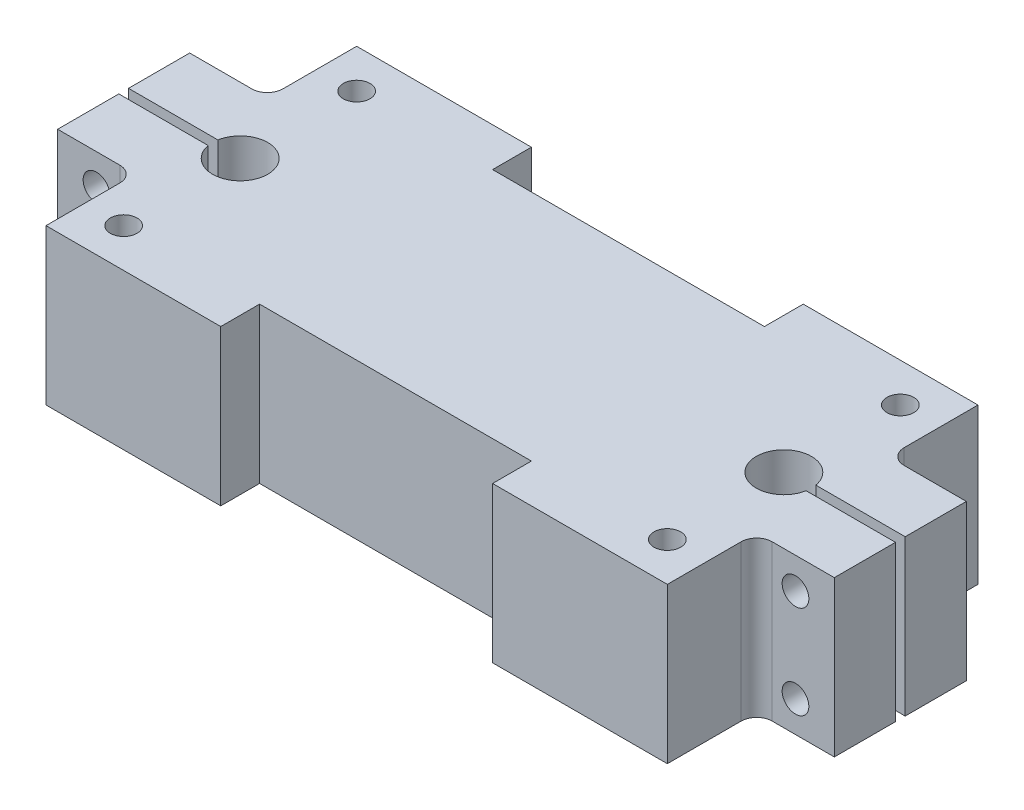
SolidWorks part; units mm, degrees
ref_plane "Front Plane" through (0, 0, 0) normal (0, 0, 1) x (1, 0, 0)
ref_plane "Top Plane" through (0, 0, 0) normal (0, 1, 0) x (1, 0, 0)
ref_plane "Right Plane" through (0, 0, 0) normal (1, 0, 0) x (0, 0, -1)
sketch "Sketch1" plane through (0, 0, 0) normal (0, 1, 0) x (1, 0, 0)
  line L1 (-63.5, 25.4) -> (63.5, 25.4)
  line L2 (-63.5, 25.4) -> (-63.5, -25.4)
  line L3 (-63.5, -25.4) -> (63.5, -25.4)
  line L4 (63.5, 25.4) -> (63.5, -25.4)
  dimension "D1" = 50.8
  dimension "D2" = 127
  dimension "D3" = 63.5
  dimension "D4" = 25.4
extrude "Boss-Extrude1" add sketch "Sketch1" along normal blind 25.4 contours L2 L3 L4 L1
sketch "Sketch2" plane through (0, 25.4, 0) normal (0, 1, 0) x (1, 0, 0)
  line L0 (-63.5, 25.4) -> (-63.5, -25.4) construction
  line L1 (63.5, 25.4) -> (63.5, -25.4) construction
  line L2 (-63.5, -25.4) -> (63.5, -25.4) construction
  circle A0 centre (-44.45, 0) radius 4.5085
  circle A1 centre (44.45, 0) radius 4.5085
  point P6 (63.5, 0)
  dimension "D1" = 9.017
  dimension "D2" = 9.017
  dimension "D3" = 19.05
  dimension "D4" = 19.05
  dimension "D5" = 25.4
  dimension "D6" = 25.4
extrude "Cut-Extrude1" cut sketch "Sketch2" against normal through all
sketch "Sketch3" plane through (0, 25.4, 0) normal (0, 1, 0) x (1, 0, 0)
  line L1 (-44.45, 0.7937) -> (-63.5, 0.7937)
  line L2 (-44.45, 0.7937) -> (-44.45, -0.7938)
  line L3 (-44.45, -0.7938) -> (-63.5, -0.7938)
  line L4 (-63.5, 0.7937) -> (-63.5, -0.7938)
  line L5 (-63.5, 25.4) -> (63.5, 25.4) construction
  line L7 (63.5, 0.7937) -> (63.5, -0.7938)
  line L8 (44.45, -0.7938) -> (63.5, -0.7938)
  line L9 (44.45, 0.7937) -> (44.45, -0.7938)
  line L10 (44.45, 0.7937) -> (63.5, 0.7937)
  dimension "D1" = 0.7937
  dimension "D2" = 1.5875
  dimension "D3" = 19.05
  dimension "D4" = 44.45
  dimension "D5" = 1.5875
  dimension "D6" = 24.6062
  dimension "D7" = 19.05
  dimension "D8" = 44.45
  dimension "D9" = 1.5875
extrude "Cut-Extrude2" cut sketch "Sketch3" against normal through all
sketch "Sketch4" plane through (0, 25.4, 0) normal (0, 1, 0) x (1, 0, 0)
  line L1 (-63.5, 25.4) -> (-50.8, 25.4)
  line L2 (-63.5, 25.4) -> (-63.5, 10.795)
  line L3 (-63.5, 10.795) -> (-50.8, 10.795)
  line L4 (-50.8, 25.4) -> (-50.8, 10.795)
  line L5 (-63.5, -25.4) -> (-50.8, -25.4)
  line L6 (-63.5, -25.4) -> (-63.5, -10.795)
  line L7 (-63.5, -10.795) -> (-50.8, -10.795)
  line L8 (-50.8, -25.4) -> (-50.8, -10.795)
  line L9 (0, 25.4) -> (0, -25.4)
  line L10 (-63.5, 25.4) -> (63.5, 25.4) construction
  line L11 (-63.5, -25.4) -> (63.5, -25.4) construction
  line L12 (50.8, -25.4) -> (50.8, -10.795)
  line L13 (63.5, -10.795) -> (50.8, -10.795)
  line L14 (63.5, -25.4) -> (63.5, -10.795)
  line L15 (63.5, -25.4) -> (50.8, -25.4)
  line L16 (50.8, 25.4) -> (50.8, 10.795)
  line L17 (63.5, 10.795) -> (50.8, 10.795)
  line L18 (63.5, 25.4) -> (63.5, 10.795)
  line L19 (63.5, 25.4) -> (50.8, 25.4)
  line M3 (63.5, 0.7937) -> (63.5, 25.4)
  line M4 (63.5, 25.4) -> (-63.5, 25.4)
  line M5 (-63.5, 25.4) -> (-63.5, 0.7937)
  line M9 (-63.5, -0.7938) -> (-63.5, -25.4)
  line M10 (-63.5, -25.4) -> (63.5, -25.4)
  line M11 (63.5, -25.4) -> (63.5, -0.7938)
  dimension "D1" = 12.7
  dimension "D2" = 21.59
  dimension "D3" = 14.605
  dimension "D4" = 0
extrude "Cut-Extrude3" cut sketch "Sketch4" against normal through all contours L8 L7 M10 M9 | L4 L3 M4 M5 | L17 L16 M3 M4 | L13 L12 M11 M10
sketch "Sketch5" plane through (0, 0, 10.795) normal (0, 0, 1) x (1, 0, 0)
  line L0 (-57.15, 25.4) -> (-57.15, 0)
  line L1 (-63.5, 25.4) -> (-50.8, 25.4) construction
  line L2 (-63.5, 0) -> (-50.8, 0) construction
  line L3 (57.15, 25.4) -> (57.15, 0)
  line L4 (63.5, 25.4) -> (50.8, 25.4) construction
  line L5 (63.5, 0) -> (50.8, 0) construction
  point P12 (-57.15, 20.32)
  point P13 (-57.15, 5.08)
  point P14 (57.15, 5.08)
  point P15 (57.15, 20.32)
  dimension "D1" = 5.08
  dimension "D2" = 5.08
  dimension "D3" = 5.08
  dimension "D4" = 5.08
hole_wizard "11/64 (0.17188) Diameter Hole1" positions "3DSketch1" profile "Sketch6" hole size "11/64" standard "ANSI Inch"
sketch3d "3DSketch1"
  point P0 (-57.15, 20.32, 10.795)
  point P3 (-57.15, 5.08, 10.795)
  point P6 (57.15, 20.32, 10.795)
  point P9 (57.15, 5.08, 10.795)
sketch "Sketch6" plane through (-57.15, 20.32, 10.795) normal (1, 0, 0) x (0, -1, 0)
  line L0 (0, 0) -> (0, 26.7116)
  line L1 (0, 26.7116) -> (2.1829, 25.4)
  line L2 (2.1829, 25.4) -> (2.1829, 0)
  line L5 (2.1829, 0) -> (0, 0)
  line L10 (0, 26.7116) -> (-2.1829, 25.4) construction
  line L11 (0, -6.35) -> (0, 107.95) construction
  dimension "Hole Dia." = 4.3658
  dimension "Hole Depth" = 25.4
  dimension "Drill Angle" = 118
fillet "Fillet3" radius 2.54 4 edges at (50.8, 12.7, 10.795) (50.8, 12.7, -10.795) (-50.8, 12.7, -10.795) (-50.8, 12.7, 10.795)
sketch "Sketch7" plane through (0, 25.4, 0) normal (0, 1, 0) x (1, 0, 0)
  line L0 (-44.45, 25.4) -> (-44.45, -25.4)
  line L1 (-50.8, 25.4) -> (50.8, 25.4) construction
  line L2 (-50.8, -25.4) -> (50.8, -25.4) construction
  line L3 (44.45, 0) -> (44.45, 25.4)
  line L4 (44.45, 25.4) -> (44.45, -25.4)
  point P7 (-44.45, 19.05)
  point P8 (-44.45, -19.05)
  point P12 (44.45, 19.05)
  point P14 (44.45, -19.05)
  dimension "D1" = 6.35
  dimension "D2" = 6.35
  dimension "D3" = 6.35
  dimension "D4" = 6.35
hole_wizard "11/64 (0.17188) Diameter Hole2" positions "3DSketch2" profile "Sketch8" hole size "11/64" standard "ANSI Inch"
sketch3d "3DSketch2"
  point P0 (-44.45, 25.4, -19.05)
  point P3 (-44.45, 25.4, 19.05)
  point P6 (44.45, 25.4, 19.05)
  point P9 (44.45, 25.4, -19.05)
sketch "Sketch8" plane through (-44.45, 25.4, -19.05) normal (1, 0, 0) x (0, 0, 1)
  line L0 (0, 0) -> (0, 26.7116)
  line L1 (0, 26.7116) -> (2.1829, 25.4)
  line L2 (2.1829, 25.4) -> (2.1829, 0)
  line L5 (2.1829, 0) -> (0, 0)
  line L10 (0, 26.7116) -> (-2.1829, 25.4) construction
  line L11 (0, -6.35) -> (0, 107.95) construction
  dimension "Hole Dia." = 4.3658
  dimension "Hole Depth" = 25.4
  dimension "Drill Angle" = 118
sketch "Sketch9" plane through (0, 25.4, 0) normal (0, 1, 0) x (1, 0, 0)
  line L0 (-50.8, -25.4) -> (50.8, -25.4) construction
  line L1 (-22.225, -19.05) -> (22.225, -19.05)
  line L2 (-22.225, -19.05) -> (-22.225, -25.4)
  line L3 (-22.225, -25.4) -> (22.225, -25.4)
  line L4 (22.225, -19.05) -> (22.225, -25.4)
  line L5 (22.225, -19.05) -> (22.225, -44.45) construction
  line L6 (22.225, 19.05) -> (22.225, 44.45) construction
  line L7 (-22.225, 19.05) -> (22.225, 19.05)
  line L8 (-22.225, 19.05) -> (-22.225, 25.4)
  line L9 (-22.225, 25.4) -> (22.225, 25.4)
  line L10 (22.225, 19.05) -> (22.225, 25.4)
  line L11 (-50.8, 25.4) -> (50.8, 25.4) construction
extrude "Cut-Extrude4" cut sketch "Sketch9" against normal through all
